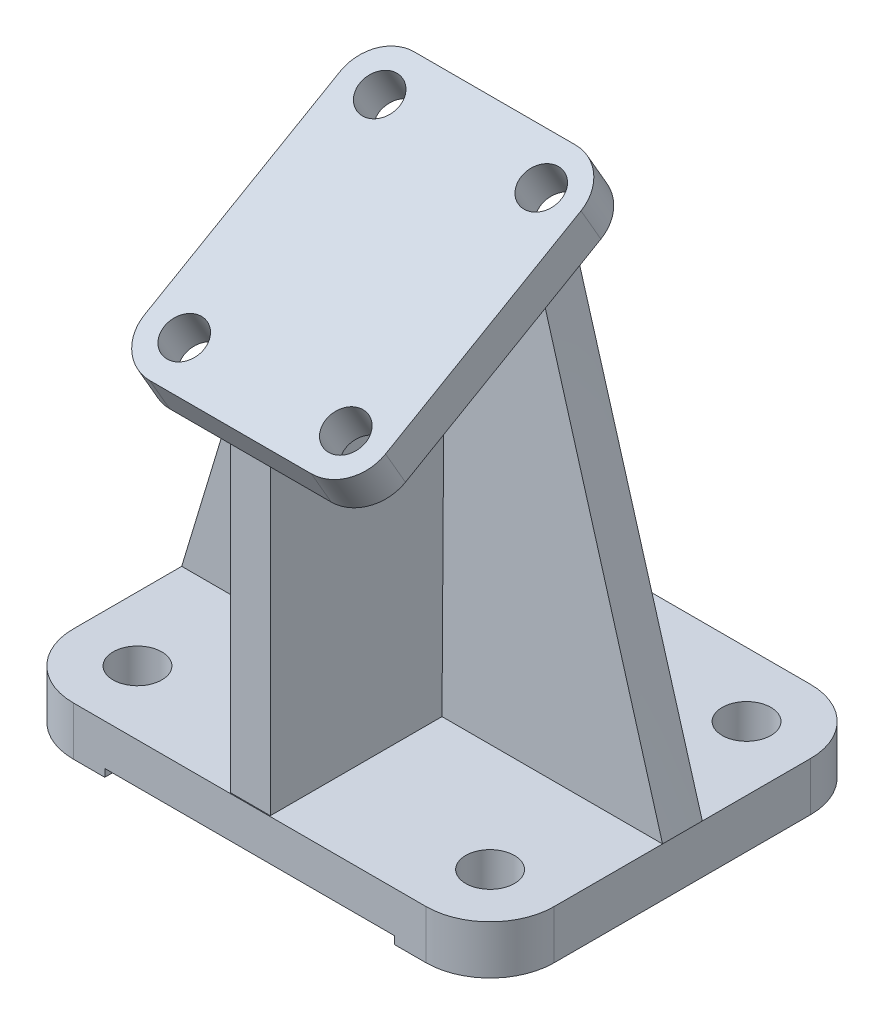
SolidWorks part; units mm, degrees
ref_plane "Front Plane" through (0, 0, 0) normal (0, 0, 1) x (1, 0, 0)
ref_plane "Top Plane" through (0, 0, 0) normal (0, 1, 0) x (1, 0, 0)
ref_plane "Right Plane" through (0, 0, 0) normal (1, 0, 0) x (0, 0, -1)
sketch "Sketch1" plane through (0, 0, 0) normal (0, 1, 0) x (1, 0, 0)
  line L1 (-47.625, 38.1) -> (47.625, 38.1)
  line L2 (-47.625, 38.1) -> (-47.625, -38.1)
  line L3 (-47.625, -38.1) -> (47.625, -38.1)
  line L4 (47.625, 38.1) -> (47.625, -38.1)
  line L5 (-47.625, 38.1) -> (47.625, -38.1) construction
  line L6 (-47.625, -38.1) -> (47.625, 38.1) construction
  point P0 (0, 0)
  dimension "D1" = 76.2
  dimension "D2" = 95.25
extrude "Boss-Extrude1" add sketch "Sketch1" along normal blind 9.652
fillet "Fillet1" radius 12.7 4 edges at (-47.625, 4.826, 38.1) (-47.625, 4.826, -38.1) (47.625, 4.826, -38.1) (47.625, 4.826, 38.1)
sketch "Sketch2" plane through (0, 9.652, 0) normal (0, 1, 0) x (1, 0, 0)
  circle A0 centre (-34.925, -25.4) radius 4.826
  circle A1 centre (-34.925, 25.4) radius 4.826
  circle A2 centre (34.925, 25.4) radius 4.826
  circle A3 centre (34.925, -25.4) radius 4.826
  arc A4 (-47.625, -25.4) -> (-34.925, -38.1) centre (-34.925, -25.4) ccw construction
  dimension "D1" = 9.652
extrude "Cut-Extrude1" cut sketch "Sketch2" against normal through all and the other way through all
sketch "Sketch3" plane through (0, 0, 38.1) normal (0, 0, 1) x (1, 0, 0)
  line L1 (-28.702, 1.524) -> (28.702, 1.524)
  line L2 (-28.702, 1.524) -> (-28.702, -1.524)
  line L3 (-28.702, -1.524) -> (28.702, -1.524)
  line L4 (28.702, 1.524) -> (28.702, -1.524)
  line L5 (-28.702, 1.524) -> (28.702, -1.524) construction
  line L6 (-28.702, -1.524) -> (28.702, 1.524) construction
  line L8 (-34.925, 0) -> (34.925, 0) construction
  point P6 (0, 0)
  point P7 (0, 0)
  dimension "D1" = 3.048
  dimension "D2" = 57.404
extrude "Cut-Extrude2" cut sketch "Sketch3" against normal through all
sketch "Sketch4" plane through (0, 0, 0) normal (1, 0, 0) x (0, 0, -1)
  line L0 (-37.9366, 9.4833) -> (-37.9366, 69.4845) construction
  line L1 (-37.9366, 69.4845) -> (3.3326, 93.3113) construction
  point P2 (0, 0)
  dimension "D1" = 120
ref_plane "Plane1" through (0, 68.5404, 39.5718) normal (0, -0.866, -0.5) x (0, 0.5, -0.866)
sketch "Sketch5" plane through (0, 68.5404, 39.5718) normal (0, -0.866, -0.5) x (0, 0.5, -0.866)
  line L1 (62.3402, 23.876) -> (1.8882, 23.876)
  line L2 (62.3402, 23.876) -> (62.3402, -23.876)
  line L3 (62.3402, -23.876) -> (1.8882, -23.876)
  line L4 (1.8882, 23.876) -> (1.8882, -23.876)
  point P4 (1.8882, 0)
  dimension "D1" = 47.752
  dimension "D2" = 60.452
extrude "Boss-Extrude2" add sketch "Sketch5" against normal blind 7.874 separate body
fillet "Fillet2" radius 7.874 4 edges at (23.876, 103.1201, -12.4478) (-23.876, 72.8941, 39.9051) (-23.876, 103.1201, -12.4478) (23.876, 72.8941, 39.9051)
sketch "Sketch6" plane through (0, 75.3595, 43.5088) normal (0, 0.866, 0.5) x (1, 0, 0)
  circle A0 centre (-16.002, 9.7622) radius 3.937
  circle A1 centre (16.002, 9.7622) radius 3.937
  circle A2 centre (16.002, 54.4662) radius 3.937
  circle A3 centre (-16.002, 54.4662) radius 3.937
  dimension "D1" = 7.874
extrude "Cut-Extrude3" cut sketch "Sketch6" against normal blind 7.874
sketch "Sketch7" plane through (0, 9.652, 0) normal (0, 1, 0) x (1, 0, 0)
  line L0 (-47.625, 0) -> (47.625, 0) construction
  line L1 (-47.625, 25.4) -> (-47.625, -25.4) construction
  line L2 (47.625, -25.4) -> (47.625, 25.4) construction
  line L3 (-47.625, -3.937) -> (47.625, -3.937)
  line L4 (-47.625, 3.937) -> (47.625, 3.937)
  line L5 (47.625, -3.937) -> (47.625, 3.937)
  line L6 (-47.625, -3.937) -> (-47.625, 3.937)
  dimension "D1" = 3.937
  dimension "D2" = 3.937
sketch "Sketch8" plane through (0, 0, 0) normal (0, 0, 1) x (1, 0, 0)
  line L0 (47.625, 9.652) -> (23.876, 91.3872) construction
  point P3 (0, 0)
  point P4 (0, 0)
sketch "Sketch9" plane through (0, 68.5404, 39.5718) normal (0, -0.866, -0.5) x (1, 0, 0)
  line L0 (23.876, -54.4662) -> (23.876, -9.7622) construction
  line L1 (23.876, -49.6306) -> (-23.876, -49.6306)
  line L2 (23.876, -49.6306) -> (23.876, -41.7566)
  line L3 (23.876, -41.7566) -> (-23.876, -41.7566)
  line L4 (-23.876, -49.6306) -> (-23.876, -41.7566)
  line L5 (-23.876, -9.7622) -> (-23.876, -54.4662) construction
  point P9 (23.876, -45.6936)
  dimension "D1" = 7.874
loft "Loft1" add profiles "Sketch9", "Sketch7"
sketch "Sketch10" plane through (0, 0, 0) normal (1, 0, 0) x (0, 0, -1)
  line L0 (-37.9366, 9.4833) -> (-37.9366, 69.4845) construction
  line L1 (-37.9366, 9.4833) -> (-37.9366, 69.4845)
rib "Rib1" sketch "Sketch10" sketch "Sketch10" thickness 7.874 extrusion direction parallel to sketch draft on no parameters "D1"=7.874
